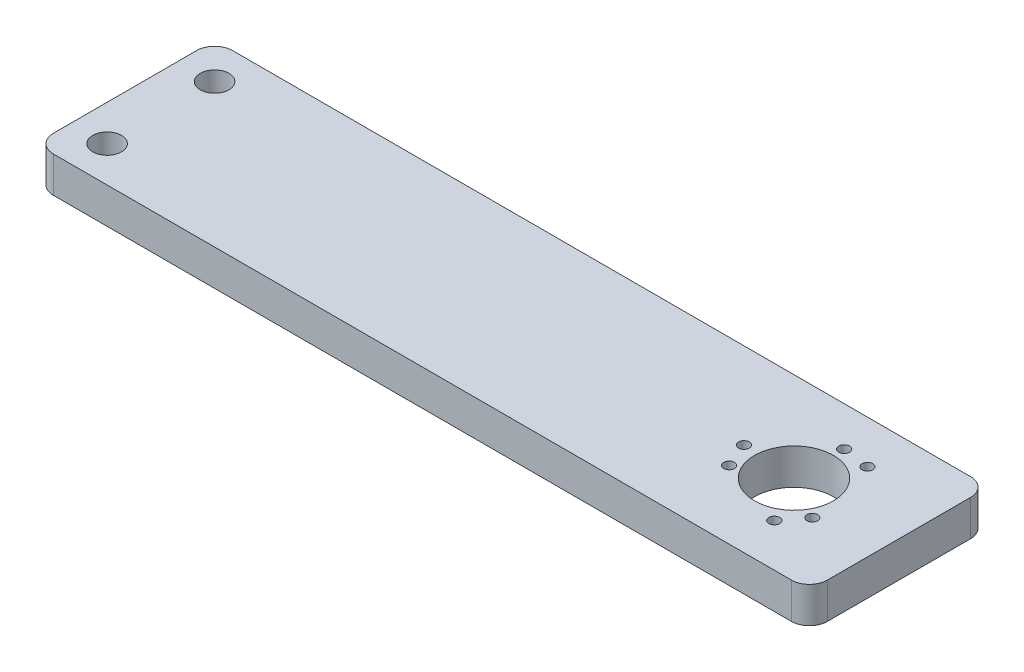
SolidWorks part; units mm, degrees
ref_plane "Front Plane" through (0, 0, 0) normal (0, 0, 1) x (1, 0, 0)
ref_plane "Top Plane" through (0, 0, 0) normal (0, 1, 0) x (1, 0, 0)
ref_plane "Right Plane" through (0, 0, 0) normal (1, 0, 0) x (0, 0, -1)
sketch "Sketch1" plane through (0, 0, 0) normal (0, 1, 0) x (1, 0, 0)
  line L1 (-103, -25) -> (103, -25)
  line L2 (-108, -20) -> (-108, 20)
  line L3 (-103, 25) -> (103, 25)
  line L4 (108, -20) -> (108, 20)
  line L5 (-108, -25) -> (108, 25) construction
  line L6 (-108, 25) -> (108, -25) construction
  arc A0 (103, 25) -> (108, 20) centre (103, 20) cw
  arc A1 (103, -25) -> (108, -20) centre (103, -20) ccw
  arc A2 (-103, -25) -> (-108, -20) centre (-103, -20) cw
  arc A3 (-108, 20) -> (-103, 25) centre (-103, 20) cw
  circle A4 centre (-98, 15) radius 4
  circle A5 centre (-98, -15) radius 4
  circle A6 centre (78.7, 0) radius 11
  circle A7 centre (78.7, 0) radius 19.3
  circle A8 centre (78.7, 14) radius 1.5
  circle A9 centre (86.2, 12.9904) radius 1.5
  circle A10 centre (90.8244, -7) radius 1.5
  circle A11 centre (86.2, -12.9904) radius 1.5
  circle A12 centre (63.7, 1.0089) radius 1.5
  circle A13 centre (66.5756, -5.9911) radius 1.5
  point P0 (0, 0)
  point P28 (78.7, 14)
  point P29 (86.2, 12.9904)
  point P30 (90.8244, -7)
  point P31 (86.2, -12.9904)
  point P32 (66.5756, -5.9911)
  point P33 (63.7, 1.0089)
  dimension "D3" = 5
  dimension "D4" = 8
  dimension "D5" = 8
  dimension "D10" = 22
  dimension "D11" = 38.6
  dimension "D13" = 14
  dimension "D24" = 3
  dimension "D25" = 3
  dimension "D26" = 3
  dimension "D27" = 3
  dimension "D28" = 3
  dimension "D29" = 3
  dimension "D1" = 216
  dimension "D2" = 50
  dimension "D6" = 10
  dimension "D7" = 10
  dimension "D8" = 10
  dimension "D9" = 10
  dimension "D12" = 176.7
  dimension "D14" = 7.5
  dimension "D15" = 12.9904
  dimension "D16" = 7.5677
  dimension "D17" = 12.1244
  dimension "D18" = 7.5
  dimension "D19" = 7.5
  dimension "D20" = 15
  dimension "D21" = 15
  dimension "D22" = 7
  dimension "D23" = 12.1244
extrude "Boss-Extrude1" add sketch "Sketch1" along normal blind 10 contours L3 A0 L4 A1 L1 A2 L2 A3 | A4 | A5 | A6 | A13 | A12 | A8 | A9 | A10 | A11
